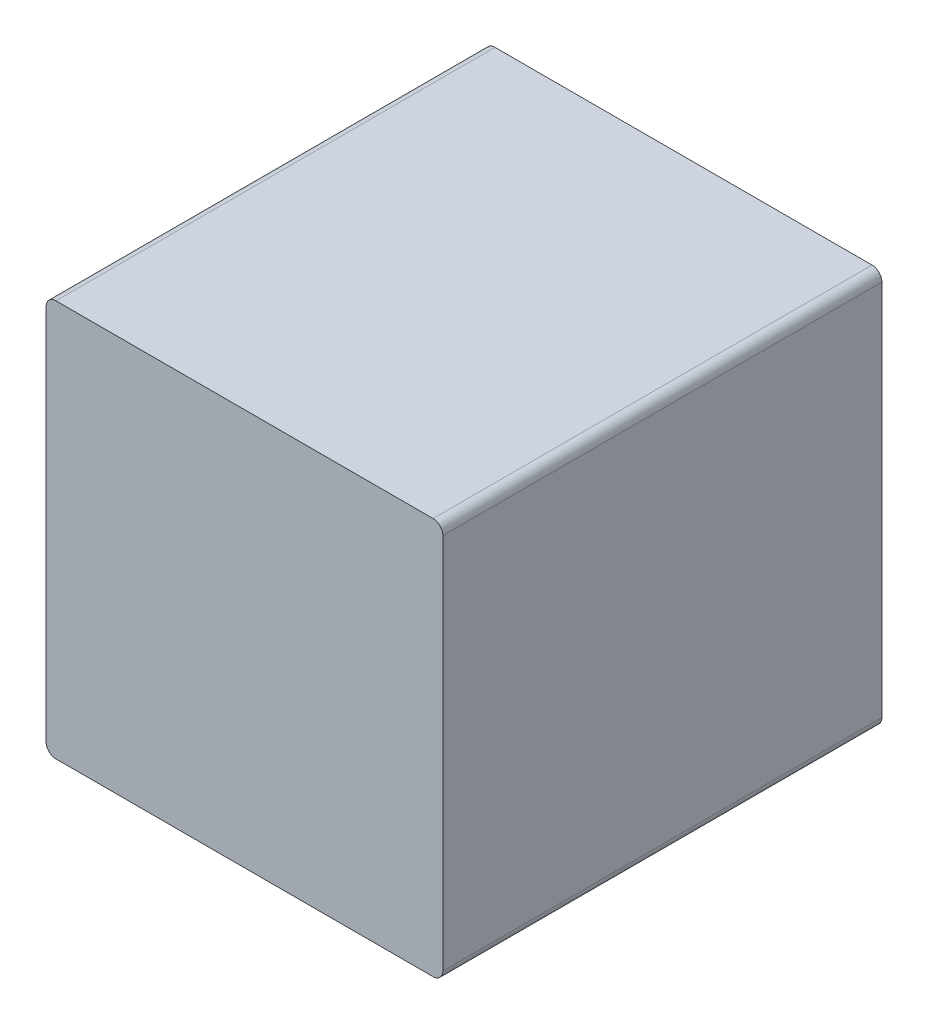
SolidWorks part; units mm, degrees
ref_plane "前视基准面" through (0, 0, 0) normal (0, 0, 1) x (1, 0, 0)
ref_plane "上视基准面" through (0, 0, 0) normal (0, 1, 0) x (1, 0, 0)
ref_plane "右视基准面" through (0, 0, 0) normal (1, 0, 0) x (0, 0, -1)
other "Configuration Table"
sketch "草图1" plane through (0, 0, 0) normal (0, 0, 1) x (1, 0, 0)
  line L0 (-5.755, -6.055) -> (5.755, -6.055)
  line L1 (6.055, -5.755) -> (6.055, 5.755)
  line L2 (5.755, 6.055) -> (-5.755, 6.055)
  line L3 (-6.055, 5.755) -> (-6.055, -5.755)
  arc A0 (5.755, -6.055) -> (6.055, -5.755) centre (5.755, -5.755) ccw
  arc A1 (6.055, 5.755) -> (5.755, 6.055) centre (5.755, 5.755) ccw
  arc A2 (-5.755, 6.055) -> (-6.055, 5.755) centre (-5.755, 5.755) ccw
  arc A3 (-6.055, -5.755) -> (-5.755, -6.055) centre (-5.755, -5.755) ccw
extrude "Button_cap_envelope_12p11" add sketch "草图1" along normal blind 13.4
